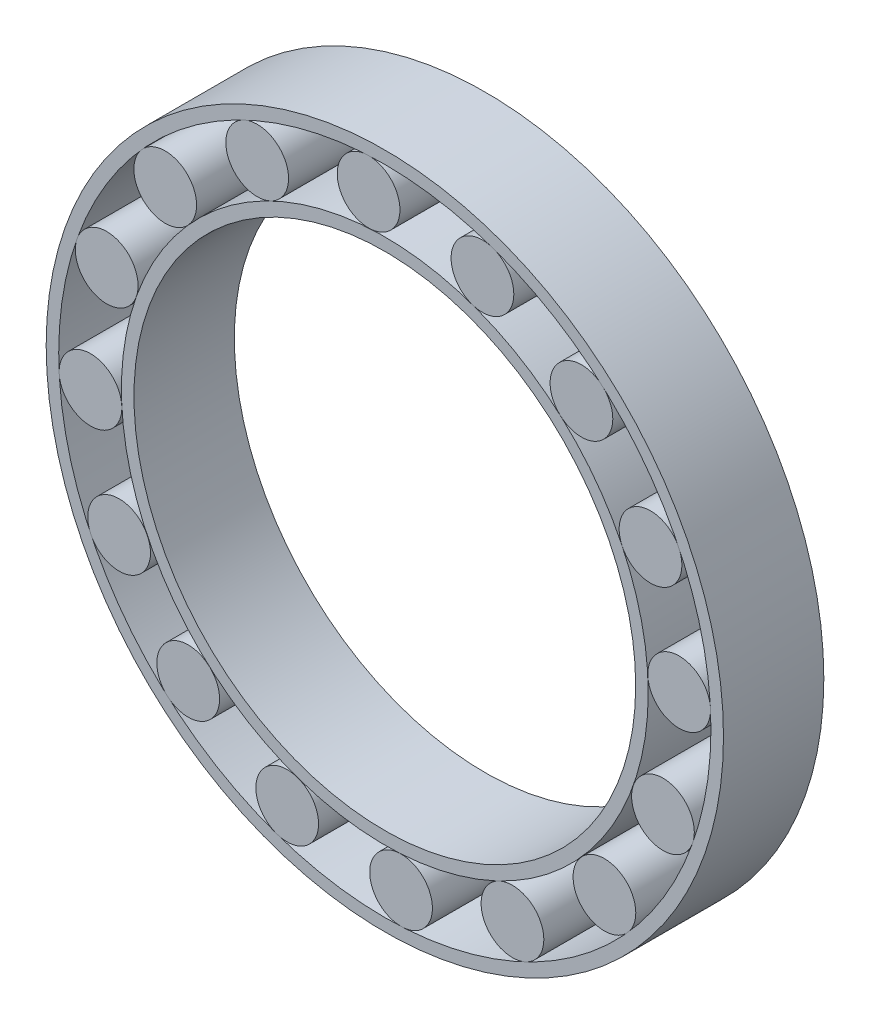
SolidWorks part; units mm, degrees
ref_plane "Ön Düzlem" through (0, 0, 0) normal (0, 0, 1) x (1, 0, 0)
ref_plane "Üst Düzlem" through (0, 0, 0) normal (0, 1, 0) x (1, 0, 0)
ref_plane "Sağ Düzlem" through (0, 0, 0) normal (1, 0, 0) x (0, 0, -1)
sketch "Çizim1" plane through (0, 0, 0) normal (0, 0, 1) x (1, 0, 0)
  circle A0 centre (0, 0) radius 13.5
  circle A1 centre (0, 0) radius 10
  circle A3 centre (0, 0) radius 13
  circle A4 centre (0, 0) radius 10.5
  circle A5 centre (-0.6474, 11.7322) radius 1.25
  circle A6 centre (3.8916, 11.0868) radius 1.25
  circle A7 centre (7.8381, 8.7537) radius 1.25
  circle A8 centre (10.5913, 5.0878) radius 1.25
  circle A9 centre (11.7322, 0.6474) radius 1.25
  circle A10 centre (11.0868, -3.8916) radius 1.25
  circle A11 centre (8.7537, -7.8381) radius 1.25
  circle A12 centre (5.0878, -10.5913) radius 1.25
  circle A13 centre (0.6474, -11.7322) radius 1.25
  circle A14 centre (-3.8916, -11.0868) radius 1.25
  circle A15 centre (-7.8381, -8.7537) radius 1.25
  circle A16 centre (-10.5913, -5.0878) radius 1.25
  circle A17 centre (-11.7322, -0.6474) radius 1.25
  circle A18 centre (-11.0868, 3.8916) radius 1.25
  circle A19 centre (-8.7537, 7.8381) radius 1.25
  circle A20 centre (-5.0878, 10.5913) radius 1.25
  point P40 (0, 0)
  dimension "D1" = 27
  dimension "D2" = 20
  dimension "D3" = 21
  dimension "D4" = 26
  dimension "D5" = 2.5
  dimension "D6" = 16
extrude "Yükseklik-Ekstrüzyon1" add sketch "Çizim1" along normal blind 4 contours A0 A3 | A4 A1 | A20 | A5 | A6 | A19 | A18 | A17 | A16 | A15 | A14 | A13 | A12 | A11 | A10 | A9 | A8 | A7 A3
